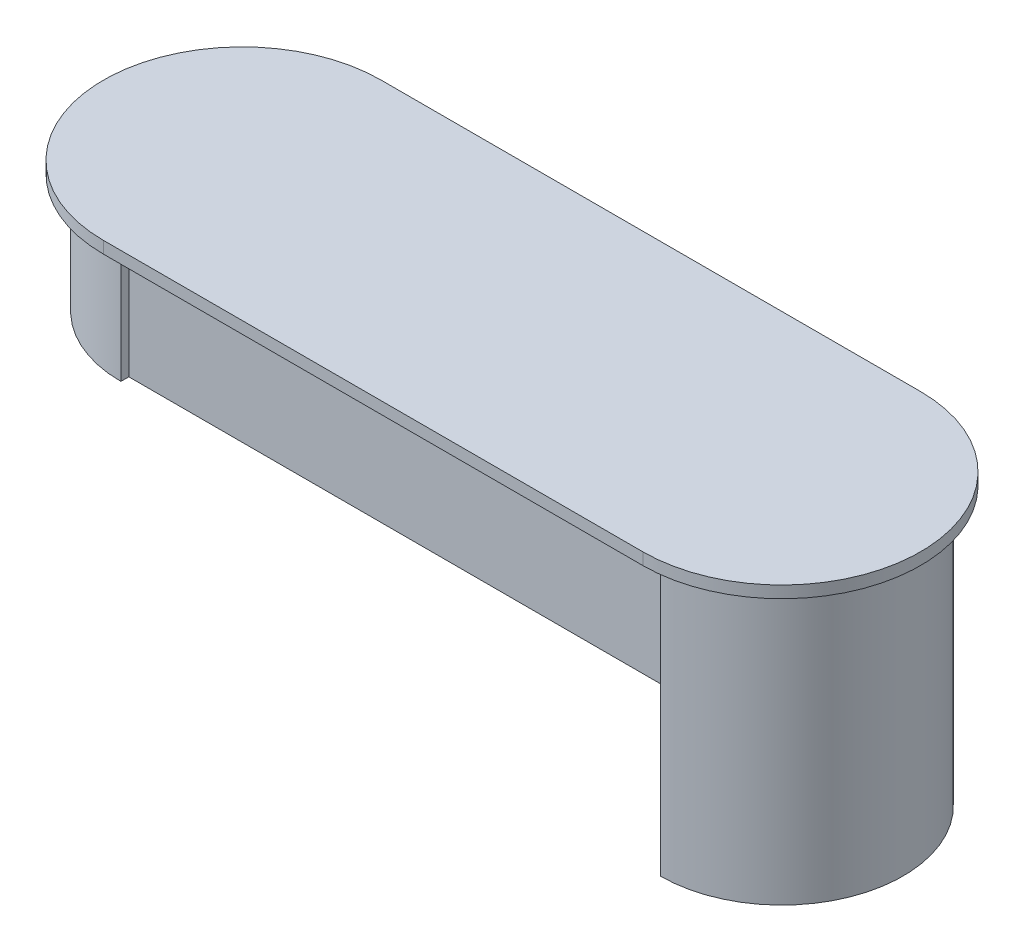
SolidWorks part; units mm, degrees
ref_plane "Front Plane" through (0, 0, 0) normal (0, 0, 1) x (1, 0, 0)
ref_plane "Top Plane" through (0, 0, 0) normal (0, 1, 0) x (1, 0, 0)
ref_plane "Right Plane" through (0, 0, 0) normal (1, 0, 0) x (0, 0, -1)
sketch "Эскиз1" plane through (0, 0, 0) normal (0, 1, 0) x (1, 0, 0)
  line L0 (0, 0) -> (13.6, 0) construction
  line L1 (0, 3.06) -> (13.6, 3.06)
  line L2 (0, -3.06) -> (13.6, -3.06)
  arc A0 (0, 3.06) -> (0, -3.06) centre (0, 0) ccw
  arc A1 (13.6, -3.06) -> (13.6, 3.06) centre (13.6, 0) ccw
  point P3 (6.8, 0)
  dimension "D2" = 3.06
  dimension "D1" = 13.6
extrude "Вытянуть-Тонкостенный1" add sketch "Эскиз1" along normal blind 3 thin
sketch "Эскиз2" plane through (0, 3, 0) normal (0, 1, 0) x (1, 0, 0)
  line L0 (0, 0) -> (13.6, 0) construction
  line L1 (0, 3.5) -> (13.6, 3.5)
  line L2 (0, -3.5) -> (13.6, -3.5)
  arc A0 (0, 3.5) -> (0, -3.5) centre (0, 0) ccw
  arc A1 (13.6, -3.5) -> (13.6, 3.5) centre (13.6, 0) ccw
  point P4 (6.8, 0)
  dimension "D1" = 3.5
extrude "Бобышка-Вытянуть1" add sketch "Эскиз2" along normal blind 0.3
sketch "Эскиз3" plane through (0, 3, 0) normal (0, -1, 0) x (1, 0, 0)
  line L0 (0, -2.26) -> (2, -2.26)
  line L1 (13.6, -2.26) -> (0, -2.26) construction
  line L2 (2, -2.26) -> (2, 2.26)
  line L3 (0, 2.26) -> (13.6, 2.26) construction
  line L4 (2, 2.26) -> (0, 2.26)
  arc A0 (0, 2.26) -> (0, -2.26) centre (0, 0) ccw construction
  arc A1 (0, 2.26) -> (0, -2.26) centre (0, 0) ccw
  dimension "D1" = 2
extrude "Бобышка-Вытянуть2" add sketch "Эскиз3" along normal offset from surface (2.5 mm away) 0.5 up to face at (6.8, 0, 0)
sketch "Эскиз4" plane through (0, 0, -2.26) normal (0, 0, 1) x (1, 0, 0)
  line L0 (2, 3) -> (0.2, 3)
  line L1 (0.2, 3) -> (2, 1.2)
  line L3 (2, 1.2) -> (2, 3)
  point P3 (0, 0)
  dimension "D1" = 1.8
  dimension "D2" = 45
extrude "Вырез-Вытянуть1" cut sketch "Эскиз4" along normal up to surface (4.52 mm away) up to face at (5.2, 1.1667, 2.26)
sketch "Эскиз5" plane through (0, 0, 0) normal (0, -1, 0) x (1, 0, 0)
  arc A0 (13.6, -2.26) -> (13.6, 2.26) centre (13.6, 0) ccw construction
  arc A1 (13.6, -2.26) -> (13.6, 2.26) centre (13.6, 0) ccw
extrude "Вытянуть-Тонкостенный2" add sketch "Эскиз5" along normal blind 4 thin
sketch "Эскиз6" plane through (0, 0, 0) normal (0, -1, 0) x (1, 0, 0)
  line L1 (13.6, 3.06) -> (0, 3.06)
  line L2 (13.6, 3.06) -> (13.6, 2.86)
  line L3 (13.6, 2.86) -> (0, 2.86)
  line L4 (0, 3.06) -> (0, 2.86)
  line L5 (13.6, -3.06) -> (0, -3.06)
  line L6 (13.6, -3.06) -> (13.6, -2.86)
  line L7 (13.6, -2.86) -> (0, -2.86)
  line L8 (0, -3.06) -> (0, -2.86)
  dimension "D1" = 0.2
  dimension "D2" = 0.2
extrude "Вырез-Вытянуть2" cut sketch "Эскиз6" against normal up to surface (3 mm away) up to face at (6.8, 3, 0)
